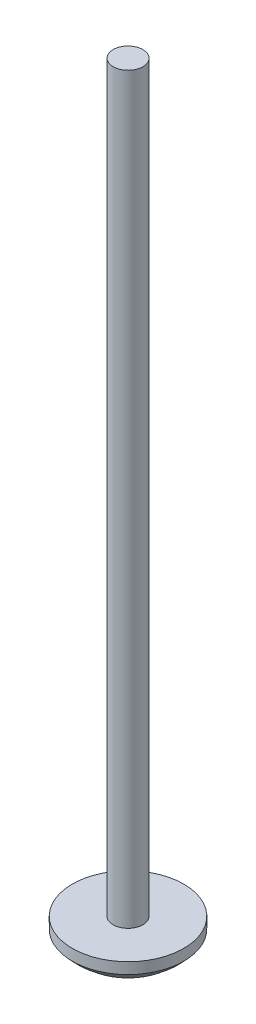
SolidWorks part; units mm, degrees
ref_plane "Front Plane" through (0, 0, 0) normal (0, 0, 1) x (1, 0, 0)
ref_plane "Top Plane" through (0, 0, 0) normal (0, 1, 0) x (1, 0, 0)
ref_plane "Right Plane" through (0, 0, 0) normal (1, 0, 0) x (0, 0, -1)
sketch "Sketch1" plane through (0, 0, 0) normal (0, 0, 1) x (1, 0, 0)
  line L0 (0, 0) -> (0, 22.8391) construction
  line L1 (-1.5, 0.7) -> (-1.5, 1)
  line L2 (-1.5, 1) -> (-0.4, 1)
  line L3 (-0.4, 1) -> (-0.4, 21)
  line L4 (-0.4, 21) -> (0, 21)
  line L5 (0, 0) -> (-2.9492, 0) construction
  line L6 (0, 0) -> (0, 21)
  arc A0 (0, 0) -> (-1.5, 0.7) centre (0, 1.9571) cw
  point P10 (0, 18.3291)
  point P11 (0, 22.8391)
  dimension "D1" = 3
  dimension "D2" = 1
  dimension "D3" = 0.3
  dimension "D4" = 0.8
  dimension "D5" = 21
revolve "Revolve1" add sketch "Sketch1" angle 360 about L6
ref_plane "Plane1" through (0, 11, 0) normal (0, 1, 0) x (1, 0, 0)
